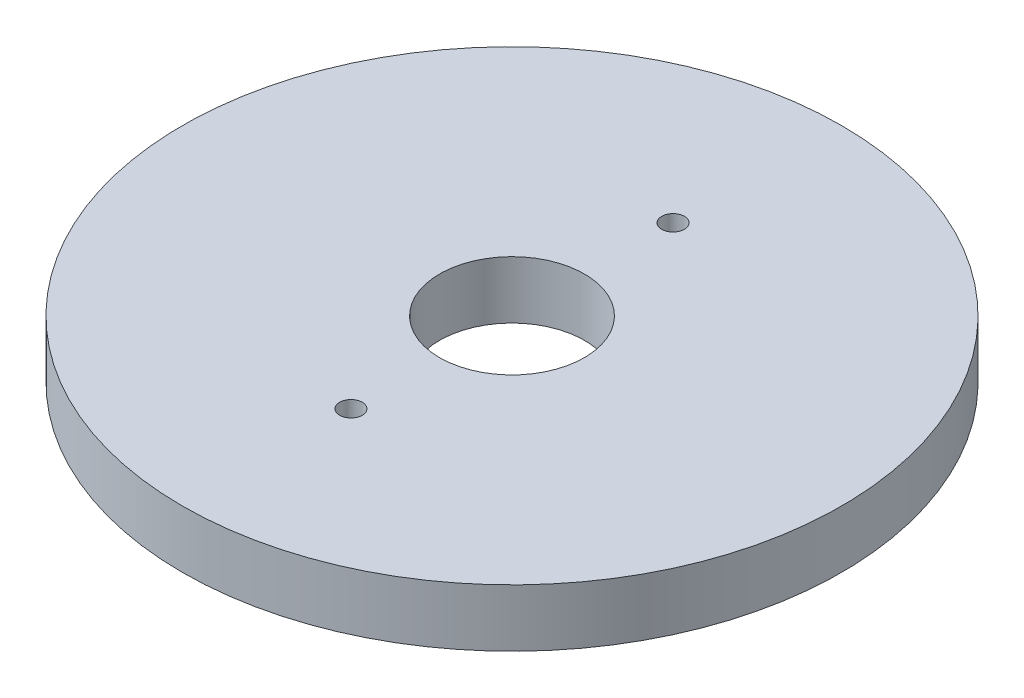
SolidWorks part; units mm, degrees
ref_plane "Front Plane" through (0, 0, 0) normal (0, 0, 1) x (1, 0, 0)
ref_plane "Top Plane" through (0, 0, 0) normal (0, 1, 0) x (1, 0, 0)
ref_plane "Right Plane" through (0, 0, 0) normal (1, 0, 0) x (0, 0, -1)
sketch "Sketch1" plane through (0, 0, 0) normal (0, 1, 0) x (1, 0, 0)
  circle A0 centre (0, 0) radius 36.3855
  dimension "D1" = 72.771
extrude "Boss-Extrude1" add sketch "Sketch1" along normal blind 6.35
hole_wizard "Tap Drill for M3x0.5 Tap2" positions "Sketch6" profile "Sketch5" hole size "M3x0.5" standard "ANSI Metric"
sketch "Sketch6" plane through (0, 6.35, 0) normal (0, 1, 0) x (1, 0, 0)
  line L0 (0, 0) -> (24.6222, 0) construction
  point P0 (0, 17.78)
  point P9 (0, -17.78)
  dimension "D1" = 35.56
sketch "Sketch5" plane through (0, 6.35, -17.78) normal (1, 0, 0) x (0, 0, 1)
  line L0 (0, 0) -> (0, 3.9261)
  line L1 (0, 3.9261) -> (1.25, 3.175)
  line L2 (1.25, 3.175) -> (1.25, 0)
  line L5 (1.25, 0) -> (0, 0)
  line L10 (0, 3.9261) -> (-1.25, 3.175) construction
  line L11 (0, -6.35) -> (0, 107.95) construction
  dimension "Hole Dia." = 2.5
  dimension "Hole Depth" = 3.175
  dimension "Drill Angle" = 118
sketch "Sketch7" plane through (0, 6.35, 0) normal (0, 1, 0) x (1, 0, 0)
  circle A0 centre (0, 0) radius 8.001
  dimension "D1" = 16.002
extrude "Cut-Extrude1" cut sketch "Sketch7" against normal through all
